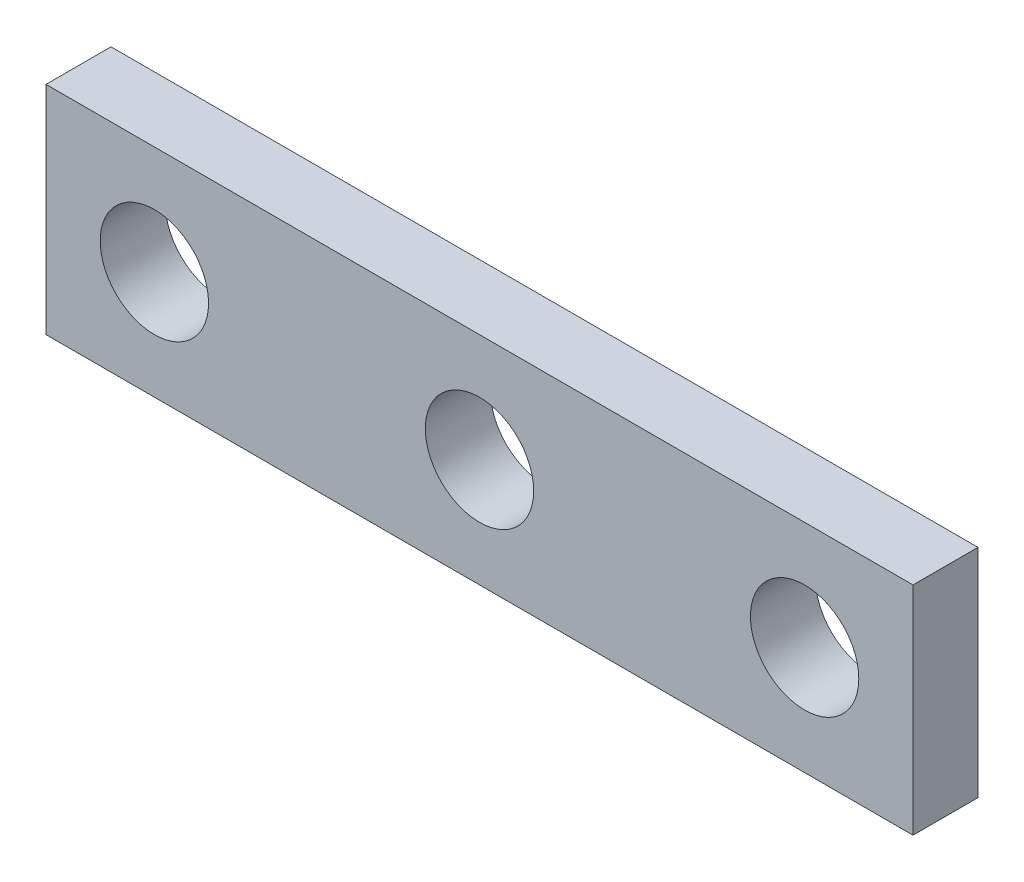
SolidWorks part; units mm, degrees
ref_plane "前基準面" through (0, 0, 0) normal (0, 0, 1) x (1, 0, 0)
ref_plane "上基準面" through (0, 0, 0) normal (0, 1, 0) x (1, 0, 0)
ref_plane "右基準面" through (0, 0, 0) normal (1, 0, 0) x (0, 0, -1)
sketch "草圖1" plane through (0, 0, 0) normal (0, 0, 1) x (1, 0, 0)
  line L0 (-20, 0) -> (20, 0) construction
  line L1 (-20, -5) -> (20, -5)
  line L2 (-20, -5) -> (-20, 5)
  line L3 (-20, 5) -> (20, 5)
  line L4 (20, -5) -> (20, 5)
  line L5 (-20, -5) -> (20, 5) construction
  line L6 (-20, 5) -> (20, -5) construction
  circle A0 centre (-15, 0) radius 2.5
  circle A1 centre (15, 0) radius 2.5
  circle A2 centre (0, 0) radius 2.5
  point P0 (0, 0)
  dimension "D5" = 5
  dimension "D6" = 5
  dimension "D7" = 5
  dimension "D1" = 10
  dimension "D2" = 40
  dimension "D3" = 15
  dimension "D4" = 15
extrude "填料-伸長1" add sketch "草圖1" along normal blind 3
